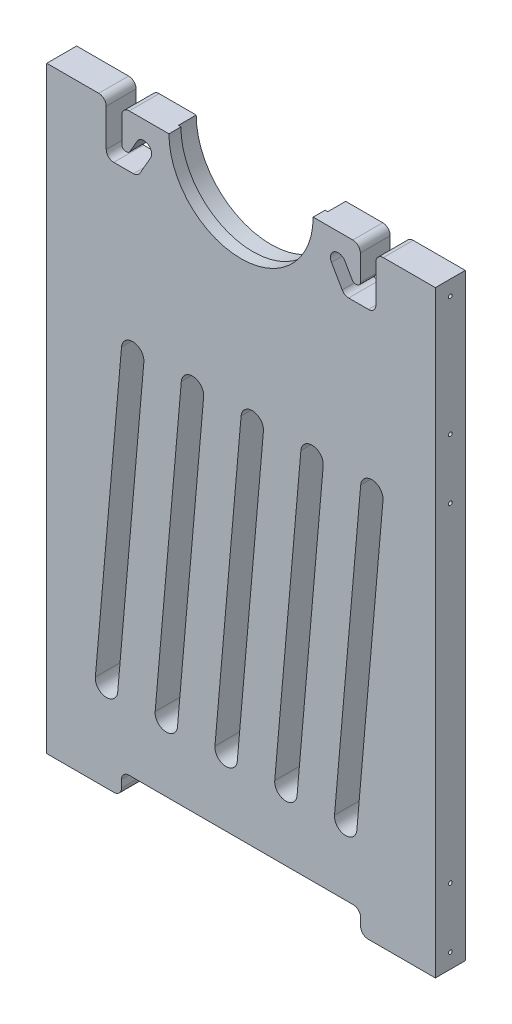
SolidWorks part; units mm, degrees
material "Delrin 2700 NC010, Low Viscosity Acetal Copolymer (SS)"
ref_plane "Front Plane" through (0, 0, 0) normal (0, 0, 1) x (1, 0, 0)
ref_plane "Top Plane" through (0, 0, 0) normal (0, 1, 0) x (1, 0, 0)
ref_plane "Right Plane" through (0, 0, 0) normal (1, 0, 0) x (0, 0, -1)
sketch "Sketch1" plane through (0, 0, 0) normal (0, 1, 0) x (1, 0, 0)
  line L1 (-82.55, -6.35) -> (82.55, -6.35)
  line L2 (-82.55, -6.35) -> (-82.55, 6.35)
  line L3 (-82.55, 6.35) -> (82.55, 6.35)
  line L4 (82.55, -6.35) -> (82.55, 6.35)
  line L5 (-82.55, -6.35) -> (82.55, 6.35) construction
  line L6 (-82.55, 6.35) -> (82.55, -6.35) construction
  point P0 (0, 0)
  dimension "D1" = 165.1
  dimension "D2" = 12.7
extrude "Boss-Extrude1" add sketch "Sketch1" along normal mid plane 254
sketch "Sketch2" plane through (0, 0, 6.35) normal (0, 0, 1) x (1, 0, 0)
  line L0 (-82.55, 127) -> (82.55, 127) construction
  circle A0 centre (0, 127) radius 30.6349
  dimension "D1" = 61.2699
extrude "Cut-Extrude1" cut sketch "Sketch2" against normal through all
sketch "Sketch3" plane through (0, 0, -6.35) normal (0, 0, -1) x (-1, 0, 0)
  circle A0 centre (0, 127) radius 31.75
  dimension "D1" = 63.5
extrude "Cut-Extrude2" cut sketch "Sketch3" against normal blind 7.62
sketch "Sketch4" plane through (0, 0, 6.35) normal (0, 0, 1) x (1, 0, 0)
  line L0 (57.277, 127) -> (57.277, 104.775)
  line L1 (30.6349, 127) -> (82.55, 127) construction
  line L2 (57.277, 104.775) -> (43.878, 104.775)
  line L3 (43.878, 104.775) -> (38.4154, 114.2365)
  line L5 (44.1346, 117.5385) -> (47.6908, 111.379)
  line L6 (47.6908, 111.379) -> (50.673, 111.379)
  line L7 (50.673, 111.379) -> (50.673, 127)
  line L8 (50.673, 127) -> (57.277, 127)
  line L9 (82.55, 127) -> (82.55, -127) construction
  line L10 (0, 0) -> (0, 185.1482) construction
  line L11 (-50.673, 127) -> (-57.277, 127)
  line L12 (-50.673, 111.379) -> (-50.673, 127)
  line L13 (-47.6908, 111.379) -> (-50.673, 111.379)
  line L14 (-44.1346, 117.5385) -> (-47.6908, 111.379)
  line L15 (-43.878, 104.775) -> (-38.4154, 114.2365)
  line L16 (-57.277, 104.775) -> (-43.878, 104.775)
  line L17 (-57.277, 127) -> (-57.277, 104.775)
  arc A0 (44.1346, 117.5385) -> (38.4154, 114.2365) centre (41.275, 115.8875) ccw
  arc A1 (-44.1346, 117.5385) -> (-38.4154, 114.2365) centre (-41.275, 115.8875) cw
  point P6 (53.975, 127)
  point P13 (41.1467, 109.5058)
  dimension "D8" = 3.302
  dimension "D1" = 6.604
  dimension "D2" = 28.575
  dimension "D3" = 22.225
  dimension "D4" = 120
  dimension "D5" = 6.604
  dimension "D6" = 6.604
  dimension "D7" = 12.7
  dimension "D9" = 11.1125
extrude "Cut-Extrude3" cut sketch "Sketch4" against normal through all
fillet "Fillet1" radius 3.175 8 edges at (-57.277, 104.775, 0) (-43.878, 104.775, 0) (-57.277, 127, 0) (-50.673, 127, 0) (50.673, 127, 0) (57.277, 127, 0) (57.277, 104.775, 0) (43.878, 104.775, 0)
fillet "Fillet2" radius 1.5875 4 edges at (-50.673, 111.379, 0) (-47.6908, 111.379, 0) (47.6908, 111.379, 0) (50.673, 111.379, 0)
sketch "Sketch5" plane through (0, 0, 6.35) normal (0, 0, 1) x (1, 0, 0)
  line L0 (-82.55, -127) -> (82.55, -127) construction
  line L1 (-50.8, -127) -> (50.8, -127)
  line L2 (-50.8, -127) -> (-50.8, -117.475)
  line L3 (-50.8, -117.475) -> (50.8, -117.475)
  line L4 (50.8, -127) -> (50.8, -117.475)
  point P6 (0, -127)
  point P7 (0, -127)
  dimension "D1" = 9.525
  dimension "D2" = 101.6
extrude "Cut-Extrude4" cut sketch "Sketch5" against normal through all
fillet "Fillet3" radius 3.175 4 edges at (50.8, -127, 0) (50.8, -117.475, 0) (-50.8, -117.475, 0) (-50.8, -127, 0)
hole_wizard "1/16 (0.0625) Diameter Hole1" positions "Sketch6" profile "Sketch7" hole size "1/16" standard "ANSI Inch"
sketch "Sketch6" plane through (82.55, 0, 0) normal (1, 0, 0) x (0, 0, -1)
  line L0 (-6.35, -127) -> (6.35, -127) construction
  point P0 (0, -120.65)
  point P2 (0, -95.25)
  point P4 (0, 44.45)
  point P6 (0, 69.85)
  point P8 (0, 120.65)
  point P13 (0, -127)
  dimension "D1" = 0
other "AlignGroup1" parameters "D1"=0, "D2"=6.35, "D3"=31.75, "D4"=171.45, "D5"=196.85, "D6"=247.65
sketch "Sketch7" plane through (82.55, -120.65, 0) normal (0, 1, 0) x (0, 0, -1)
  line L0 (0, 0) -> (0, 16.3519)
  line L1 (0, 16.3519) -> (0.7937, 15.875)
  line L2 (0.7937, 15.875) -> (0.7937, 0)
  line L5 (0.7937, 0) -> (0, 0)
  line L10 (0, 16.3519) -> (-0.7938, 15.875) construction
  line L11 (0, -6.35) -> (0, 107.95) construction
  dimension "Hole Dia." = 1.5875
  dimension "Hole Depth" = 15.875
  dimension "Drill Angle" = 118
hole_wizard "1/16 (0.0625) Diameter Hole2" positions "Sketch8" profile "Sketch9" hole size "1/16" standard "ANSI Inch"
sketch "Sketch8" plane through (-82.55, 0, 0) normal (-1, 0, 0) x (0, 0, 1)
  point P0 (0, -120.65)
  point P3 (0, -95.25)
  point P6 (0, 44.45)
  point P9 (0, 69.85)
  point P12 (0, 120.65)
sketch "Sketch9" plane through (-82.55, -120.65, 0) normal (0, 1, 0) x (0, 0, 1)
  line L0 (0, 0) -> (0, 16.3519)
  line L1 (0, 16.3519) -> (0.7937, 15.875)
  line L2 (0.7937, 15.875) -> (0.7937, 0)
  line L5 (0.7937, 0) -> (0, 0)
  line L10 (0, 16.3519) -> (-0.7937, 15.875) construction
  line L11 (0, -6.35) -> (0, 107.95) construction
  dimension "Hole Dia." = 1.5875
  dimension "Hole Depth" = 15.875
  dimension "Drill Angle" = 118
sketch "Sketch10" plane through (0, 0, 6.35) normal (0, 0, 1) x (1, 0, 0)
  line L0 (-57.15, -88.9) -> (-46.0389, 38.1) construction
  line L1 (-61.8944, -88.4849) -> (-50.7833, 38.5151)
  line L2 (-52.4056, -89.3151) -> (-41.2946, 37.6849)
  line L3 (-82.55, -127) -> (-53.975, -127) construction
  line L4 (-82.55, 127) -> (-82.55, -127) construction
  line L5 (-27.0056, -89.3151) -> (-15.8946, 37.6849)
  line L6 (-36.4944, -88.4849) -> (-25.3833, 38.5151)
  line L7 (-31.75, -88.9) -> (-20.6389, 38.1) construction
  line L8 (-1.6056, -89.3151) -> (9.5054, 37.6849)
  line L9 (-11.0944, -88.4849) -> (0.0167, 38.5151)
  line L10 (-6.35, -88.9) -> (4.7611, 38.1) construction
  line L11 (23.7944, -89.3151) -> (34.9054, 37.6849)
  line L12 (14.3056, -88.4849) -> (25.4167, 38.5151)
  line L13 (19.05, -88.9) -> (30.1611, 38.1) construction
  line L14 (49.1944, -89.3151) -> (60.3054, 37.6849)
  line L15 (39.7056, -88.4849) -> (50.8167, 38.5151)
  line L16 (44.45, -88.9) -> (55.5611, 38.1) construction
  line L17 (-52.4056, -89.3151) -> (-27.0056, -89.3151) construction
  arc A0 (-61.8944, -88.4849) -> (-52.4056, -89.3151) centre (-57.15, -88.9) ccw
  arc A1 (-41.2946, 37.6849) -> (-50.7833, 38.5151) centre (-46.0389, 38.1) ccw
  arc A2 (-36.4944, -88.4849) -> (-27.0056, -89.3151) centre (-31.75, -88.9) ccw
  arc A3 (-15.8946, 37.6849) -> (-25.3833, 38.5151) centre (-20.6389, 38.1) ccw
  arc A4 (-11.0944, -88.4849) -> (-1.6056, -89.3151) centre (-6.35, -88.9) ccw
  arc A5 (9.5054, 37.6849) -> (0.0167, 38.5151) centre (4.7611, 38.1) ccw
  arc A6 (14.3056, -88.4849) -> (23.7944, -89.3151) centre (19.05, -88.9) ccw
  arc A7 (34.9054, 37.6849) -> (25.4167, 38.5151) centre (30.1611, 38.1) ccw
  arc A8 (39.7056, -88.4849) -> (49.1944, -89.3151) centre (44.45, -88.9) ccw
  arc A9 (60.3054, 37.6849) -> (50.8167, 38.5151) centre (55.5611, 38.1) ccw
  point P2 (-51.5945, -25.4)
  point P15 (-26.1945, -25.4)
  point P22 (-0.7945, -25.4)
  point P29 (24.6055, -25.4)
  point P36 (50.0055, -25.4)
  dimension "D3" = 4.7625
  dimension "D1" = 38.1
  dimension "D2" = 25.4
  dimension "D4" = 127
  dimension "D5" = 5
  dimension "D7" = 25.4
  dimension "D6" = 5
extrude "Cut-Extrude5" cut sketch "Sketch10" against normal through all
equation "\"D1@Sketch2\"=1.2061*2"
equation "\"D1@Sketch3\"=1.250*2"
equation "\"D8@Sketch4\"=.260/2"
